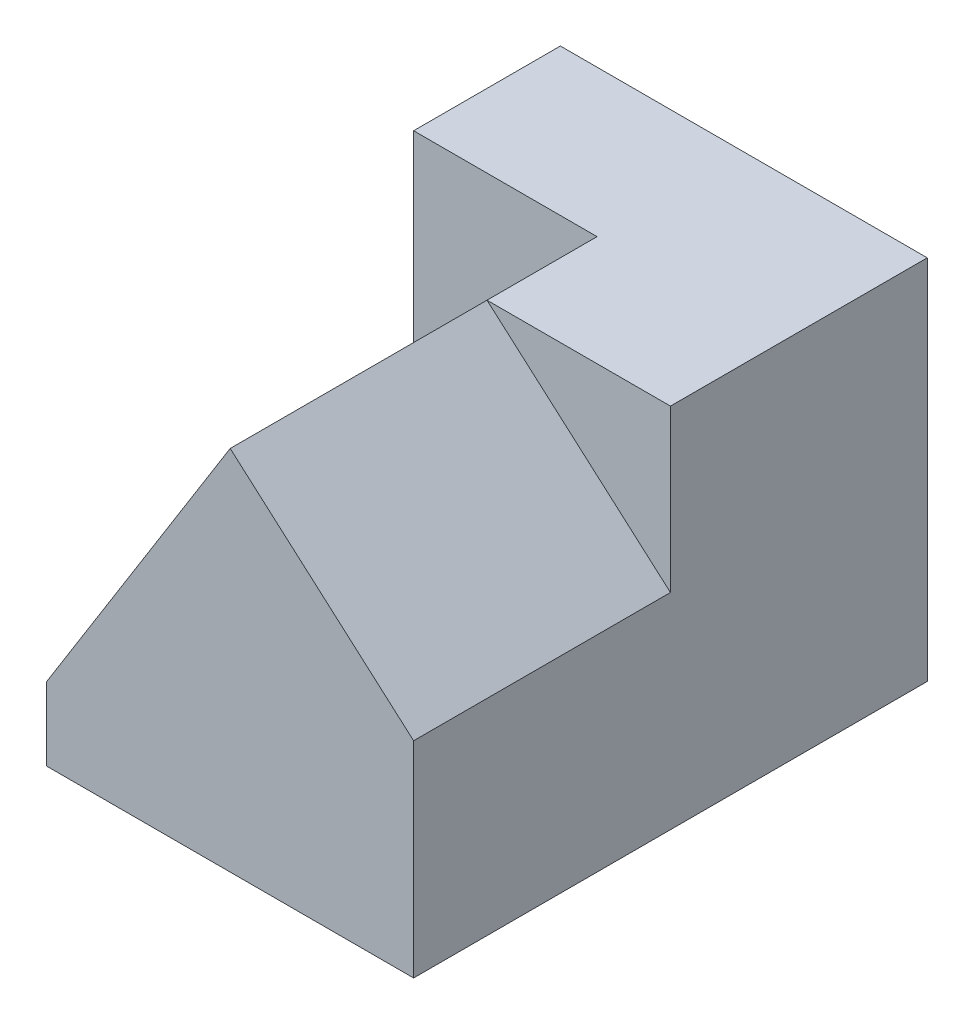
SolidWorks part; units mm, degrees
ref_plane "Front Plane" through (0, 0, 0) normal (0, 0, 1) x (1, 0, 0)
ref_plane "Top Plane" through (0, 0, 0) normal (0, 1, 0) x (1, 0, 0)
ref_plane "Right Plane" through (0, 0, 0) normal (1, 0, 0) x (0, 0, -1)
sketch "Sketch1" plane through (0, 0, 0) normal (0, 0, 1) x (1, 0, 0)
  line L0 (-25, 0) -> (25, 0)
  line L1 (25, 0) -> (25, 28)
  line L2 (25, 28) -> (0, 50)
  line L3 (0, 50) -> (-25, 10)
  line L4 (-25, 10) -> (-25, 0)
  point P6 (24.9039, 28)
  dimension "D1" = 10
  dimension "D2" = 28
  dimension "D3" = 50
  dimension "D4" = 25
  dimension "D5" = 50
extrude "Boss-Extrude1" add sketch "Sketch1" along normal blind 70
ref_plane "Plane1" through (0, 50, 0) normal (0, 1, 0) x (1, 0, 0)
sketch "Sketch2" plane through (0, 50, 0) normal (0, 1, 0) x (1, 0, 0)
  line L0 (25, -35) -> (25, 0)
  line L1 (25, -70) -> (25, 0) construction
  line L2 (25, 0) -> (-25, 0)
  line L3 (-25, 0) -> (-25, -20)
  line L4 (-25, -70) -> (-25, 0) construction
  line L5 (-25, -20) -> (0, -20)
  line L6 (0, -20) -> (0, -35)
  line L7 (0, -35) -> (25, -35)
  line L8 (25, -70) -> (0, -70) construction
  dimension "D1" = 25
  dimension "D2" = 35
  dimension "D3" = 20
extrude "Boss-Extrude2" add sketch "Sketch2" against normal up to surface (50 mm away) up to face at (0, 0, 35)
